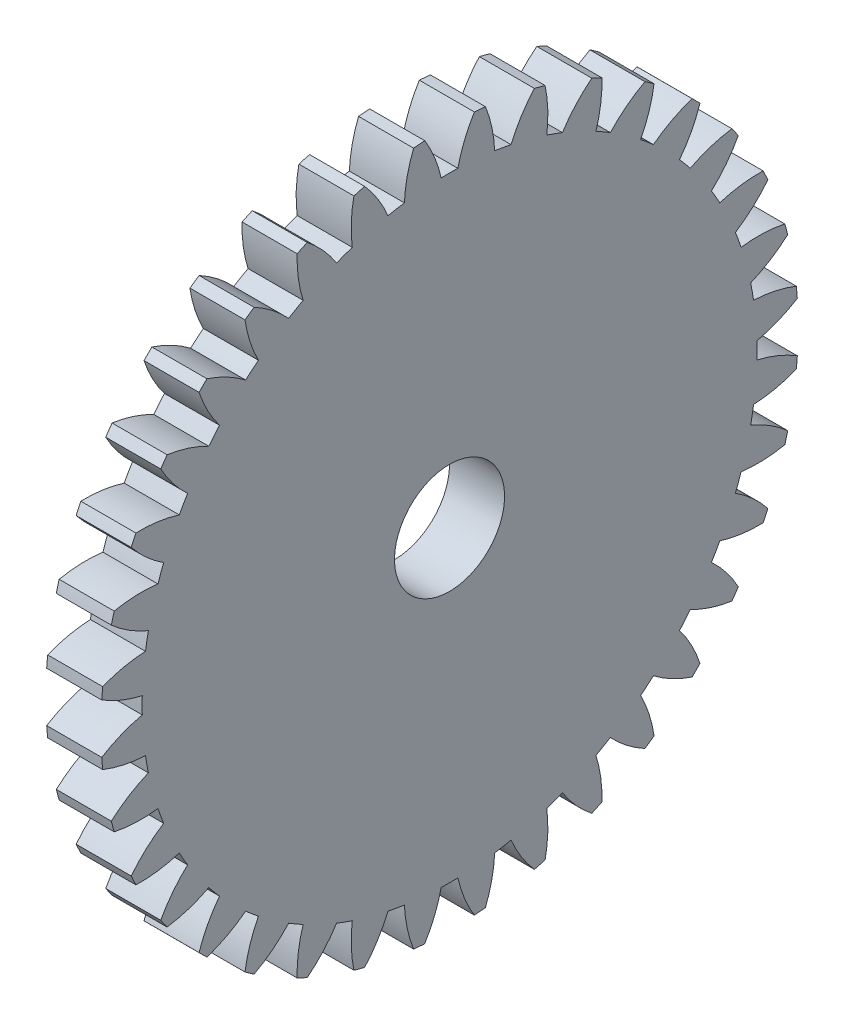
SolidWorks part; units mm, degrees
ref_plane "Plane1" through (0, 0, 0) normal (0, 0, 1) x (1, 0, 0)
ref_plane "Plane2" through (0, 0, 0) normal (0, 1, 0) x (1, 0, 0)
ref_plane "Plane3" through (0, 0, 0) normal (1, 0, 0) x (0, 0, -1)
other "Configuration Table"
sketch "HoldingSke" plane through (0, 0, 0) normal (0, 1, 0) x (1, 0, 0)
  line L0 (0, 0) -> (0.809, -0.5878)
  line L1 (-15, 0) -> (100, 0) construction
  line L2 (0, 0) -> (-2.1039, 2.3779)
  line L3 (0, 0) -> (-11.863, 4.5341)
  line L4 (0, 0) -> (6.9867, 5.0761)
  line L5 (0, 0) -> (-46.8476, -17.4728)
  line L6 (0, 0) -> (-2.4869, -1.6779)
  line L7 (-2.1039, 2.3779) -> (8.6586, 51.2059)
  line L8 (-76.2, 54.61) -> (-75.2, 54.61)
  line L9 (-71.009, 38.7566) -> (-53.1078, 45.2721)
  line L10 (-76.2, 71.12) -> (104.1128, 71.12)
  line L11 (0, 0) -> (-3, 0)
  line L12 (-76.2, 101.6) -> (-76.162, 101.6)
  line L13 (24.9733, 27.94) -> (52.9518, 28.4284)
  line L14 (24.9733, 27.94) -> (24.9743, 27.94)
  line L15 (24.9733, 27.94) -> (100.4006, 29.5858)
  line L16 (-63.627, -1) -> (-12.827, -1)
  circle A0 centre (0, 0) radius 3
  circle A1 centre (0, 0) radius 16.749
  circle A2 centre (0, 0) radius 37.5
  circle A3 centre (0, 0) radius 3
  dimension "MHD" = 33.498
  dimension "Hub_dia" = 75
  dimension "Bore" = 6
  dimension "MBD" = 6
  dimension "Num_teeth" = 36
  dimension "Pitch" = 1
  dimension "Overall_len" = 50
  dimension "Show_teeth" = 36
  dimension "Thickness" = 3
  dimension "OAL" = 50.0001
  dimension "T_dim" = 1
  dimension "Ap" = 20
  dimension "H" = 19.05
  dimension "Pitch_radius" = 180.3128
  dimension "Width" = 3
  dimension "Backlash" = 0.038
  dimension "Addendum_fac" = 1
  dimension "Dedendum_fac" = 1.25
  dimension "Clearance_fac" = 0.25
  dimension "Dedendum_add" = 0.001
  dimension "Module" = 1
sketch "BasProSke" plane through (0, 0, 0) normal (0, 1, 0) x (1, 0, 0)
  line L0 (-10, 0) -> (60, 0) construction
  line L1 (0, 0) -> (0, 19)
  line L2 (0, 0) -> (3, 0)
  line L3 (3, 0) -> (3, 19)
  line L4 (3, 19) -> (0, 19)
  dimension "Thickness" = 3
  dimension "Diameter" = 38
revolve "Base-Revolve" add sketch "BasProSke" angle 360 about L0
sketch "TooCutSke" plane through (0, 0, 0) normal (1, 0, 0) x (0, 0, -1)
  line L1 (0, 0) -> (0, 107) construction
  line L2 (0, 0) -> (-0.8516, 17.9798) construction
  line L3 (0, 0) -> (-3.1351, 35.8344) construction
  line L4 (-0.8516, 17.9798) -> (-1.5676, 17.9172) construction
  arc A0 (0.4547, 16.7428) -> (-0.4547, 16.7428) centre (0, 0) ccw
  arc A1 (1.3689, 18.9761) -> (-1.3689, 18.9761) centre (0, 0) ccw
  circle A2 centre (0, 0) radius 18 construction
  circle A3 centre (0, 0) radius 16.9145 construction
  arc A4 (-0.4547, 16.7428) -> (-1.3689, 18.9761) centre (-7.4808, 15.1702) ccw
  arc A5 (1.3689, 18.9761) -> (0.4547, 16.7428) centre (7.4808, 15.1702) ccw
  dimension "Root_dia" = 33.498
  dimension "Overcut_dia" = 38.0508
  dimension "Pitch_dia" = 36
  dimension "Base_dia" = 33.8289
  dimension "Flank_rad" = 7.2
  dimension "Half_ang" = 5
  dimension "Half_CT" = 0.7186
extrude "ToothCut" cut sketch "TooCutSke" along normal through all
fillet "Breaks" [suppressed] radius 0.02
fillet "RootFillets" [suppressed] radius 0.251
pattern_circular "TeethCuts" count 36 every 10 about axis through (-10, 0, 0) along (1, 0, 0) of "ToothCut", "RootFillets", "Breaks"
sketch "HubNeaOneSke" plane through (0, 0, 0) normal (-1, 0, 0) x (0, 0, 1)
  circle A0 centre (0, 0) radius 16.749
  dimension "Diameter" = 33.498
extrude "HubNearOne" [suppressed] add sketch "HubNeaOneSke" along normal blind 47.0001
sketch "HubNeaBotSke" plane through (0, 0, 0) normal (-1, 0, 0) x (0, 0, 1)
  circle A0 centre (0, 0) radius 16.749
  dimension "Diameter" = 33.498
extrude "HubNearBoth" [suppressed] add sketch "HubNeaBotSke" along normal blind 23.5
ref_plane "FarPln" through (3, 0, 0) normal (1, 0, 0) x (0, 0, -1)
sketch "HubFarSke" plane through (3, 0, 0) normal (1, 0, 0) x (0, 0, -1)
  circle A0 centre (0, 0) radius 16.749
  dimension "Diameter" = 33.498
extrude "HubFar" [suppressed] add sketch "HubFarSke" along normal blind 23.5
sketch "BorSke" plane through (0, 0, 0) normal (1, 0, 0) x (0, 0, -1)
  circle A0 centre (0, 0) radius 3
  dimension "Diameter" = 6
extrude "Bore" cut sketch "BorSke" along normal mid plane 100.0001
sketch "KeySke" plane through (0, 0, 0) normal (1, 0, 0) x (0, 0, -1)
  line L0 (-1, 0) -> (-1, 4)
  line L1 (-1, 4) -> (1, 4)
  line L2 (1, 4) -> (1, 0)
  line L3 (0, 0) -> (0, 34) construction
  line L4 (-1, 0) -> (1, 0)
  dimension "Offset" = 4
  dimension "Width" = 2
extrude "Keyway" [suppressed] cut sketch "KeySke" along normal mid plane 100.0001
pattern_circular "Keyway2" [suppressed] count 2 every 90 about axis through (-10, 0, 0) along (1, 0, 0)
equation "' \"Module@HoldingSke\" = 6.35"
equation "' \"Num_teeth@HoldingSke\" = 12"
equation "' \"Ap@HoldingSke\" =  20"
equation "' \"Ap@HoldingSke\" = 20"
equation "' \"Width@HoldingSke\" = 0.5 * 25.4"
equation "' \"Hub_dia@HoldingSke\"= 1 * 25.4"
equation "' \"Hub_dia@HoldingSke\" = 1 * 25.4"
equation "' \"Overall_len@HoldingSke\" = 1.0 * 25.4"
equation "' \"Bore@HoldingSke\" = 0.75 * 25.4"
equation "' \"T_dim@HoldingSke\" = 0.1 * 25.4"
equation "' \"Width@KeySke\" = 0.25 * 25.4"
equation "' \"Show_teeth@HoldingSke\" = 13"
equation "' \"Backlash@HoldingSke\" = 0.009 * 25.4"
equation "' \"Addendum_fac@HoldingSke\" = 1.0"
equation "' \"Dedendum_fac@HoldingSke\" = 1.25"
equation "' \"Dedendum_add@HoldingSke\" = 0.00005 * 25.4"
equation "' \"Clearance_fac@HoldingSke\" = 0.25"
equation "\"Pitch@HoldingSke\" = 1 / \"Module@HoldingSke\""
equation "\"Overcut_dia@TooCutSke\" = (\"Num_teeth@HoldingSke\" + 2 * \"Addendum_fac@HoldingSke\") / \"Pitch@HoldingSke\" + 0.002 * 25.4"
equation "\"Pitch_dia@TooCutSke\" = \"Num_teeth@HoldingSke\" / \"Pitch@HoldingSke\""
equation "\"Base_dia@TooCutSke\" = \"Num_teeth@HoldingSke\" / \"Pitch@HoldingSke\" * cos((\"Ap@HoldingSke\"  * 3.14159265 / 180))"
equation "\"Root_dia@TooCutSke\" = (\"Num_teeth@HoldingSke\" + 2) / \"Pitch@HoldingSke\" - 2 * (\"Addendum_fac@HoldingSke\" + \"Dedendum_fac@HoldingSke\") / \"Pitch@HoldingSke\" - \"Dedendum_add@HoldingSke\" * 2"
equation "\"Half_ang@TooCutSke\" = 180 / \"Num_teeth@HoldingSke\""
equation "\"Half_CT@TooCutSke\" = \"Num_teeth@HoldingSke\" / \"Pitch@HoldingSke\" * sin((3.14159265 / 2 / \"Num_teeth@HoldingSke\")) / 2 - 7 * \"Backlash@HoldingSke\" / 4"
equation "\"Flank_rad@TooCutSke\" = \"Num_teeth@HoldingSke\" / \"Pitch@HoldingSke\" / 5"
equation "\"Radius@RootFillets\" = \"Clearance_fac@HoldingSke\" / \"Pitch@HoldingSke\" + \"Dedendum_add@HoldingSke\""
equation "\"Break_rad@Breaks\" = 0.02 / \"Pitch@HoldingSke\""
equation "\"Thickness@HoldingSke\" = \"Width@HoldingSke\""
equation "\"OAL@HoldingSke\" = \"Thickness@HoldingSke\""
equation "\"MHD@HoldingSke\" = (\"Num_teeth@HoldingSke\" + 2) / \"Pitch@HoldingSke\" - 2 * (\"Addendum_fac@HoldingSke\" + \"Dedendum_fac@HoldingSke\")  / \"Pitch@HoldingSke\" - \"Dedendum_add@HoldingSke\" * 2"
equation "\"MBD@HoldingSke\" = (\"Num_teeth@HoldingSke\" + 2) / \"Pitch@HoldingSke\" - 2 * (\"Addendum_fac@HoldingSke\" + \"Dedendum_fac@HoldingSke\")  / \"Pitch@HoldingSke\" - \"Dedendum_add@HoldingSke\" * 2 - 0.002 * 25.4"
equation "\"MHD@HoldingSke\" = ((sgn( \"MHD@HoldingSke\" - \"Hub_dia@HoldingSke\" )-1)*( \"MHD@HoldingSke\" - \"Hub_dia@HoldingSke\" ))/-2+ \"Hub_dia@HoldingSke\""
equation "\"MBD@HoldingSke\" = ((sgn( \"MBD@HoldingSke\" - \"Bore@HoldingSke\" )-1)*( \"MBD@HoldingSke\" - \"Bore@HoldingSke\" ))/-2+ \"Bore@HoldingSke\""
equation "\"OAL@HoldingSke\" = ((sgn( \"OAL@HoldingSke\" - \"Overall_len@HoldingSke\" )+1)*( \"OAL@HoldingSke\" - \"Overall_len@HoldingSke\" ))/2 + \"Overall_len@HoldingSke\" + 0.000002 * 25.4"
equation "\"Num_teeth@TeethCuts\" = int( \"Show_teeth@HoldingSke\" ) + 1"
equation "\"Num_teeth@TeethCuts\" = ((sgn( \"Num_teeth@TeethCuts\" - \"Num_teeth@HoldingSke\" )-1)*( \"Num_teeth@TeethCuts\" - \"Num_teeth@HoldingSke\" ))/-2+ \"Num_teeth@HoldingSke\""
equation "\"Num_teeth@TeethCuts\" = ((sgn( \"Num_teeth@TeethCuts\" - 2.0)+1)*( \"Num_teeth@TeethCuts\" - 2.0))/2 +2.0"
equation "\"Angle@TeethCuts\" = 360.0 / \"Num_teeth@HoldingSke\""
equation "\"Diameter@BasProSke\" = (\"Num_teeth@HoldingSke\" + 2 * \"Addendum_fac@HoldingSke\") / \"Pitch@HoldingSke\""
equation "\"Thickness@BasProSke\"  = \"Thickness@HoldingSke\""
equation "' \"Fillet_rad@BasProSke\" =  \"Thickness@HoldingSke\" * 0.05"
equation "' \"Fillet_rad@BasProSke\" = \"Thickness@HoldingSke\" * 0.05"
equation "\"MHD@HoldingSke\" = ((sgn( \"MHD@HoldingSke\" - \"Root_dia@TooCutSke\" )-1)*( \"MHD@HoldingSke\" - \"Root_dia@TooCutSke\" ))/-2+ \"Root_dia@TooCutSke\""
equation "\"Diameter@HubNeaOneSke\" = \"MHD@HoldingSke\""
equation "\"Length@HubNearOne\" = \"OAL@HoldingSke\" - \"Thickness@BasProSke\""
equation "\"Diameter@HubNeaBotSke\" = \"MHD@HoldingSke\""
equation "\"Length@HubNearBoth\" = ( \"OAL@HoldingSke\" - \"Thickness@BasProSke\" ) / 2.0"
equation "\"Thickness@FarPln\" = \"Thickness@BasProSke\""
equation "\"Diameter@HubFarSke\" = \"MHD@HoldingSke\""
equation "\"Length@HubFar\" = ( \"OAL@HoldingSke\" - \"Thickness@BasProSke\" ) / 2.0"
equation "\"Diameter@BorSke\" = \"MBD@HoldingSke\""
equation "\"D1@Bore\" = \"OAL@HoldingSke\" * 2.0"
equation "\"D1@Keyway\" = \"OAL@HoldingSke\" * 2.0"
equation "\"Offset@KeySke\" = \"T_dim@HoldingSke\" + \"MBD@HoldingSke\" / 2.0"
